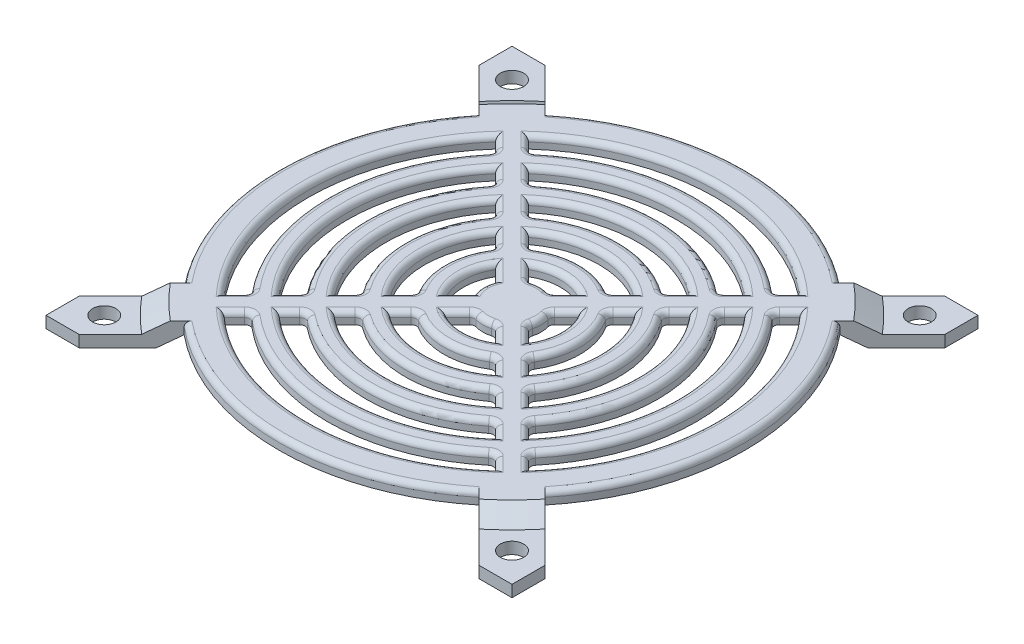
SolidWorks part; units mm, degrees
material "1.6523 (20NiCrMoS2-2)"
ref_plane "Спереди" through (0, 0, 0) normal (0, 0, 1) x (1, 0, 0)
ref_plane "Сверху" through (0, 0, 0) normal (0, 1, 0) x (1, 0, 0)
ref_plane "Справа" through (0, 0, 0) normal (1, 0, 0) x (0, 0, -1)
sketch "Эскиз1" plane through (0, 0, 0) normal (0, 1, 0) x (1, 0, 0)
  line L0 (-51.5147, -60) -> (-37.9711, -46.4564)
  line L1 (-60, 60) -> (-51.5147, 60)
  line L2 (-60, 60) -> (-60, 51.5147)
  line L3 (-60, -60) -> (-51.5147, -60)
  line L4 (60, 60) -> (60, 51.5147)
  line L5 (-60, 60) -> (60, -60) construction
  line L6 (-60, -60) -> (60, 60) construction
  line L7 (-52.5, 52.5) -> (52.5, 52.5) construction
  line L8 (-52.5, 52.5) -> (-52.5, -52.5) construction
  line L9 (-52.5, -52.5) -> (52.5, -52.5) construction
  line L10 (52.5, 52.5) -> (52.5, -52.5) construction
  line L11 (-52.5, 52.5) -> (52.5, -52.5) construction
  line L12 (-52.5, -52.5) -> (52.5, 52.5) construction
  line L13 (-60, -51.5147) -> (-46.4564, -37.9711)
  line L14 (-60, 51.5147) -> (-46.4564, 37.9711)
  line L15 (-51.5147, 60) -> (-37.9711, 46.4564)
  line L16 (14.3125, 10.0699) -> (17.8892, 13.6465)
  line L17 (2.7392, -6.9819) -> (6.4592, -10.7018)
  line L18 (51.5147, 60) -> (60, 60)
  line L19 (6.9819, -2.7392) -> (10.7018, -6.4592)
  line L20 (-60, -51.5147) -> (-60, -60)
  line L21 (6.9819, 2.7392) -> (10.7018, 6.4592)
  line L22 (-64.2426, 55.7574) -> (55.7574, -64.2426) construction
  line L23 (2.7392, 6.9819) -> (6.4592, 10.7018)
  line L24 (10.0699, 14.3125) -> (13.6465, 17.8892)
  line L25 (46.4564, -37.9711) -> (60, -51.5147)
  line L26 (-6.4592, 10.7018) -> (-2.7392, 6.9819)
  line L27 (-10.7018, 6.4592) -> (-6.9819, 2.7392)
  line L28 (-10.7018, -6.4592) -> (-6.9819, -2.7392)
  line L29 (-6.4592, -10.7018) -> (-2.7392, -6.9819)
  line L30 (10.0699, -14.3125) -> (13.6465, -17.8892)
  line L31 (14.3125, -10.0699) -> (17.8892, -13.6465)
  line L32 (21.4507, -17.2081) -> (25.0042, -20.7615)
  line L33 (28.5528, -24.3102) -> (32.0984, -27.8558)
  line L34 (35.6418, -31.3992) -> (39.1838, -34.9411)
  line L35 (17.2081, -21.4507) -> (20.7615, -25.0042)
  line L36 (24.3102, -28.5528) -> (27.8558, -32.0984)
  line L37 (31.3992, -35.6418) -> (34.9411, -39.1838)
  line L38 (-13.6465, -17.8892) -> (-10.0699, -14.3125)
  line L39 (-20.7615, -25.0042) -> (-17.2081, -21.4507)
  line L40 (-27.8558, -32.0984) -> (-24.3102, -28.5528)
  line L41 (-32.0984, -27.8558) -> (-28.5528, -24.3102)
  line L42 (-25.0042, -20.7615) -> (-21.4507, -17.2081)
  line L43 (-17.8892, -13.6465) -> (-14.3125, -10.0699)
  line L44 (-17.8892, 13.6465) -> (-14.3125, 10.0699)
  line L45 (-25.0042, 20.7615) -> (-21.4507, 17.2081)
  line L46 (-32.0984, 27.8558) -> (-28.5528, 24.3102)
  line L47 (-13.6465, 17.8892) -> (-10.0699, 14.3125)
  line L48 (-20.7615, 25.0042) -> (-17.2081, 21.4507)
  line L49 (-27.8558, 32.0984) -> (-24.3102, 28.5528)
  line L50 (21.4507, 17.2081) -> (25.0042, 20.7615)
  line L51 (28.5528, 24.3102) -> (32.0984, 27.8558)
  line L52 (35.6418, 31.3992) -> (39.1838, 34.9411)
  line L53 (31.3992, 35.6418) -> (34.9411, 39.1838)
  line L54 (17.2081, 21.4507) -> (20.7615, 25.0042)
  line L55 (24.3102, 28.5528) -> (27.8558, 32.0984)
  line L56 (-39.1838, 34.9411) -> (-35.6418, 31.3992)
  line L57 (-34.9411, 39.1838) -> (-31.3992, 35.6418)
  line L58 (-55.7574, 64.2426) -> (64.2426, -55.7574) construction
  line L59 (37.9711, -46.4564) -> (51.5147, -60)
  line L60 (-55.7574, -64.2426) -> (64.2426, 55.7574) construction
  line L61 (46.4564, 37.9711) -> (60, 51.5147)
  line L62 (-34.9411, -39.1838) -> (-31.3992, -35.6418)
  line L63 (-39.1838, -34.9411) -> (-35.6418, -31.3992)
  line L64 (-64.2426, -55.7574) -> (55.7574, 64.2426) construction
  line L65 (37.9711, 46.4564) -> (51.5147, 60)
  line L66 (60, -51.5147) -> (60, -60)
  line L67 (51.5147, -60) -> (60, -60)
  arc A0 (-2.7392, -6.9819) -> (2.7392, -6.9819) centre (0, 0) ccw
  arc A1 (-6.4592, -10.7018) -> (6.4592, -10.7018) centre (0, 0) ccw
  arc A2 (-10.0699, -14.3125) -> (10.0699, -14.3125) centre (0, 0) ccw
  arc A3 (-13.6465, -17.8892) -> (13.6465, -17.8892) centre (0, 0) ccw
  arc A4 (-17.2081, -21.4507) -> (17.2081, -21.4507) centre (0, 0) ccw
  arc A5 (-20.7615, -25.0042) -> (20.7615, -25.0042) centre (0, 0) ccw
  arc A6 (-24.3102, -28.5528) -> (24.3102, -28.5528) centre (0, 0) ccw
  arc A7 (-27.8558, -32.0984) -> (27.8558, -32.0984) centre (0, 0) ccw
  arc A8 (-31.3992, -35.6418) -> (31.3992, -35.6418) centre (0, 0) ccw
  arc A9 (-34.9411, -39.1838) -> (34.9411, -39.1838) centre (0, 0) ccw
  circle A10 centre (-52.5, -52.5) radius 3
  circle A11 centre (-52.5, 52.5) radius 3
  circle A12 centre (52.5, 52.5) radius 3
  circle A13 centre (52.5, -52.5) radius 3
  arc A14 (2.7392, 6.9819) -> (-2.7392, 6.9819) centre (0, 0) ccw
  arc A15 (6.4592, 10.7018) -> (-6.4592, 10.7018) centre (0, 0) ccw
  arc A16 (10.0699, 14.3125) -> (-10.0699, 14.3125) centre (0, 0) ccw
  arc A17 (13.6465, 17.8892) -> (-13.6465, 17.8892) centre (0, 0) ccw
  arc A18 (17.2081, 21.4507) -> (-17.2081, 21.4507) centre (0, 0) ccw
  arc A19 (20.7615, 25.0042) -> (-20.7615, 25.0042) centre (0, 0) ccw
  arc A20 (24.3102, 28.5528) -> (-24.3102, 28.5528) centre (0, 0) ccw
  arc A21 (27.8558, 32.0984) -> (-27.8558, 32.0984) centre (0, 0) ccw
  arc A22 (31.3992, 35.6418) -> (-31.3992, 35.6418) centre (0, 0) ccw
  arc A23 (34.9411, 39.1838) -> (-34.9411, 39.1838) centre (0, 0) ccw
  arc A24 (-6.9819, 2.7392) -> (-6.9819, -2.7392) centre (0, 0) ccw
  arc A25 (-10.7018, 6.4592) -> (-10.7018, -6.4592) centre (0, 0) ccw
  arc A26 (-14.3125, 10.0699) -> (-14.3125, -10.0699) centre (0, 0) ccw
  arc A27 (-17.8892, 13.6465) -> (-17.8892, -13.6465) centre (0, 0) ccw
  arc A28 (-21.4507, 17.2081) -> (-21.4507, -17.2081) centre (0, 0) ccw
  arc A29 (-25.0042, 20.7615) -> (-25.0042, -20.7615) centre (0, 0) ccw
  arc A30 (-28.5528, 24.3102) -> (-28.5528, -24.3102) centre (0, 0) ccw
  arc A31 (-32.0984, 27.8558) -> (-32.0984, -27.8558) centre (0, 0) ccw
  arc A32 (-35.6418, 31.3992) -> (-35.6418, -31.3992) centre (0, 0) ccw
  arc A33 (-39.1838, 34.9411) -> (-39.1838, -34.9411) centre (0, 0) ccw
  arc A34 (6.9819, -2.7392) -> (6.9819, 2.7392) centre (0, 0) ccw
  arc A35 (10.7018, -6.4592) -> (10.7018, 6.4592) centre (0, 0) ccw
  arc A36 (14.3125, -10.0699) -> (14.3125, 10.0699) centre (0, 0) ccw
  arc A37 (17.8892, -13.6465) -> (17.8892, 13.6465) centre (0, 0) ccw
  arc A38 (21.4507, -17.2081) -> (21.4507, 17.2081) centre (0, 0) ccw
  arc A39 (25.0042, -20.7615) -> (25.0042, 20.7615) centre (0, 0) ccw
  arc A40 (28.5528, -24.3102) -> (28.5528, 24.3102) centre (0, 0) ccw
  arc A41 (32.0984, -27.8558) -> (32.0984, 27.8558) centre (0, 0) ccw
  arc A42 (35.6418, -31.3992) -> (35.6418, 31.3992) centre (0, 0) ccw
  arc A43 (39.1838, -34.9411) -> (39.1838, 34.9411) centre (0, 0) ccw
  arc A44 (-37.9711, -46.4564) -> (37.9711, -46.4564) centre (0, 0) ccw
  arc A45 (46.4564, -37.9711) -> (46.4564, 37.9711) centre (0, 0) ccw
  arc A46 (37.9711, 46.4564) -> (-37.9711, 46.4564) centre (0, 0) ccw
  arc A47 (-46.4564, 37.9711) -> (-46.4564, -37.9711) centre (0, 0) ccw
  point P0 (0, 0)
  point P25 (-62.1213, 57.8787)
  point P26 (57.8787, -62.1213)
  point P27 (-57.8787, 62.1213)
  point P28 (62.1213, -57.8787)
  point P29 (-57.8787, -62.1213)
  point P30 (62.1213, 57.8787)
  point P31 (-62.1213, -57.8787)
  point P32 (57.8787, 62.1213)
  dimension "D3" = 15
  dimension "D4" = 25
  dimension "D5" = 35
  dimension "D6" = 45
  dimension "D7" = 55
  dimension "D8" = 65
  dimension "D9" = 75
  dimension "D10" = 85
  dimension "D11" = 95
  dimension "D12" = 105
  dimension "D15" = 6
  dimension "D16" = 6
  dimension "D17" = 6
  dimension "D18" = 6
  dimension "D1" = 120
  dimension "D2" = 120
  dimension "D13" = 105
  dimension "D14" = 105
  dimension "D19" = 6
  dimension "D20" = 6
  dimension "D21" = 6
  dimension "D22" = 6
extrude "Бобышка-Вытянуть1" add sketch "Эскиз1" along normal blind 6
sketch "Эскиз2" plane through (0, 0, 0) normal (0, -1, 0) x (1, 0, 0)
  circle A0 centre (0, 0) radius 65
  dimension "D1" = 130
extrude "Вырез-Вытянуть1" cut sketch "Эскиз2" against normal blind 3 draft 60
sketch "Эскиз3" plane through (0, 6, 0) normal (0, 1, 0) x (1, 0, 0)
  circle A0 centre (0, 0) radius 62.5
  dimension "D1" = 125
extrude "Вырез-Вытянуть2" cut sketch "Эскиз3" against normal blind 3 draft 60 flip side to cut
fillet "Скругление1" radius 1.4 81 edges at (33.1702, 6, 37.4128) (0, 6, 37.5) (-24.3102, 4.5, 28.5528) (26.083, 6, 30.3256) (0, 6, 42.5) (-31.3992, 4.5, 35.6418) (31.3992, 4.5, 35.6418) (-17.2081, 4.5, 21.4507) (-18.9848, 6, 23.2274) (0, 6, 27.5) (18.9848, 6, 23.2274) (-2.7392, 4.5, 6.9819) (0, 6, 12.5) (-4.5992, 6, 8.8418) (0, 6, 22.5) (11.8582, 6, 16.1008) (35.6418, 4.5, 31.3992) (35.6418, 4.5, -31.3992) (28.5528, 4.5, -24.3102) (21.4507, 4.5, -17.2081) (14.3125, 4.5, -10.0699) (14.3125, 4.5, 10.0699) (12.5, 6, 0) (22.5, 6, 0) (17.5, 6, 0) (32.5, 6, 0) (27.5, 6, 0) (30.3256, 6, 26.083) (23.2274, 6, 18.9848) (16.1008, 6, 11.8582) (8.8418, 6, 4.5992) (8.8418, 6, -4.5992) (16.1008, 6, -11.8582) (23.2274, 6, -18.9848) (30.3256, 6, -26.083) (37.4128, 6, -33.1702) (0, 6, 60) (-60, 6, 0) (31.3992, 4.5, -35.6418) (24.3102, 4.5, -28.5528) (17.2081, 4.5, -21.4507) (10.0699, 4.5, -14.3125) (2.7392, 4.5, -6.9819) (-2.7392, 4.5, -6.9819) (-10.0699, 4.5, -14.3125) (-17.2081, 4.5, -21.4507) (-24.3102, 4.5, -28.5528) (-31.3992, 4.5, -35.6418) (-33.1702, 6, -37.4128) (-26.083, 6, -30.3256) (-18.9848, 6, -23.2274) (-11.8582, 6, -16.1008) (11.8582, 6, -16.1008) (18.9848, 6, -23.2274) (26.083, 6, -30.3256) (33.1702, 6, -37.4128) (0, 6, -52.5) (0, 6, -47.5) (0, 6, -42.5) (0, 6, -37.5) (0, 6, -32.5) (0, 6, -27.5) (4.5992, 6, -8.8418) (0, 6, -7.5) (-30.3256, 6, 26.083) (-16.1008, 6, 11.8582) (-8.8418, 6, 4.5992) (-37.4128, 6, -33.1702) (-52.5, 6, 0) (-47.5, 6, 0) (-42.5, 6, 0) (-27.5, 6, 0) (-22.5, 6, 0) (-12.5, 6, 0) (-7.5, 6, 0) (-14.3125, 4.5, -10.0699) (-21.4507, 4.5, -17.2081) (-35.6418, 4.5, -31.3992) (-21.4507, 4.5, 17.2081) (-35.6418, 4.5, 31.3992) (-37.4128, 6, 33.1702)
